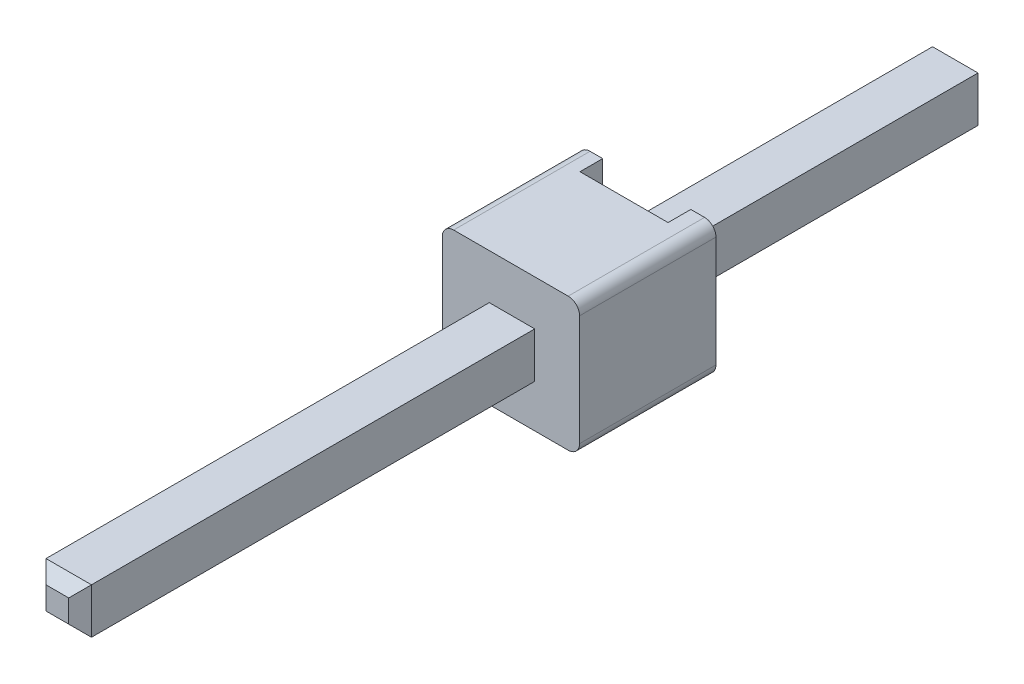
SolidWorks part; units mm, degrees
ref_plane "Front Plane" through (0, 0, 0) normal (0, 0, 1) x (1, 0, 0)
ref_plane "Top Plane" through (0, 0, 0) normal (0, 1, 0) x (1, 0, 0)
ref_plane "Right Plane" through (0, 0, 0) normal (1, 0, 0) x (0, 0, -1)
sketch "Sketch1" plane through (0, 0, 0.1788) normal (0, 1, 0) x (1, 0, 0)
  line L1 (0, 0) -> (-1.1741, 0)
  line L2 (0, 0) -> (0, -1.2076)
  line L3 (0, -1.2076) -> (-1.1741, -1.2076)
  line L4 (-1.1741, 0) -> (-1.1741, -1.2076)
extrude "Boss-Extrude1" add sketch "Sketch1" along normal blind 1.2 contours L2 L1 L4 L3
fillet "Fillet8" radius 0.1 4 edges at (-1.1741, 0.6, 1.3863) (-1.1741, 0.6, 0.1788) (0, 0.6, 0.1788) (0, 0.6, 1.3863)
sketch "Sketch2" plane through (0, 0, 0) normal (1, 0, 0) x (0, 0, -1)
  line L0 (-1.2863, 0) -> (-0.2788, 0) construction
  line L1 (-1.175, 0) -> (-0.4, 0)
  line L2 (-1.175, 0) -> (-1.175, 0.2)
  line L3 (-1.175, 0.2) -> (-0.4, 0.2)
  line L4 (-0.4, 0) -> (-0.4, 0.2)
  point P6 (-1.0957, 0.1976)
  point P7 (0, 0)
  point P8 (0, 0)
  point P9 (-1.1577, 0.1869)
  point P10 (-1.1526, 0)
  point P11 (0, 0)
  point P12 (0, 0)
  point P13 (0, 0)
  point P14 (0, 0)
extrude "Cut-Extrude2" cut sketch "Sketch2" against normal blind 1.2
sketch "Sketch7" plane through (0, 1.2, 0) normal (0, 1, 0) x (1, 0, 0)
  line L1 (-0.7602, -0.9731) -> (-0.3602, -0.9731)
  line L2 (-0.7602, -0.9731) -> (-0.7602, -0.5731)
  line L3 (-0.7602, -0.5731) -> (-0.3602, -0.5731)
  line L4 (-0.3602, -0.9731) -> (-0.3602, -0.5731)
  dimension "D1" = 0.4
  dimension "D2" = 0.4
extrude "Boss-Extrude8" add sketch "Sketch7" along normal blind 4 and the other way blind 4 separate body
chamfer "Chamfer1" distance 0.1 angle 45 4 edges at (-0.5602, 5.2, 0.9731) (-0.3602, 5.2, 0.7731) (-0.7602, 5.2, 0.7731) (-0.5602, 5.2, 0.5731)
chamfer "Chamfer2" distance 0.1 angle 45 4 edges at (-0.7602, -2.8, 0.7731) (-0.5602, -2.8, 0.9731) (-0.3602, -2.8, 0.7731) (-0.5602, -2.8, 0.5731)
move or copy body "Body-Move/Copy3" bodies to move or copy 110 107 copy no rotation origin (0.1768, 0.1495, 0.0273) rotation axis (0.5774, -0.5774, -0.5774) rotation angle 120
move or copy body "Body-Move/Copy4" bodies to move or copy 113 copy no translate (0, 0.0173, 0)
